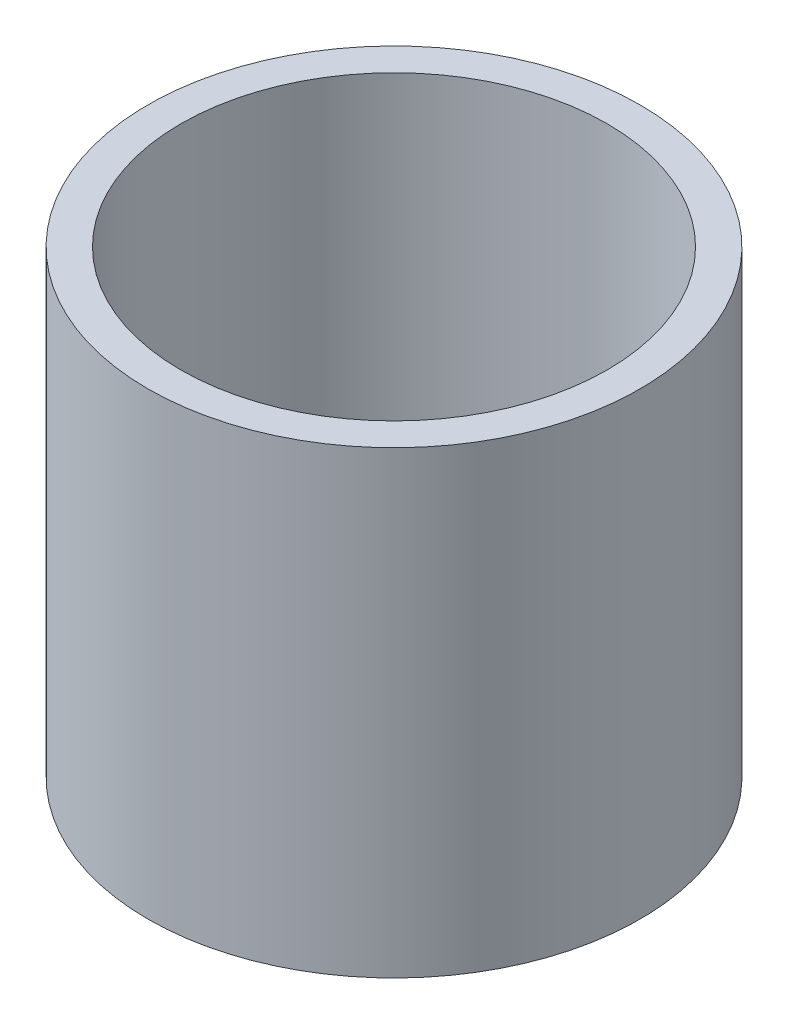
SolidWorks part; units mm, degrees
ref_plane "前视基准面" through (0, 0, 0) normal (0, 0, 1) x (1, 0, 0)
ref_plane "上视基准面" through (0, 0, 0) normal (0, 1, 0) x (1, 0, 0)
ref_plane "右视基准面" through (0, 0, 0) normal (1, 0, 0) x (0, 0, -1)
other "Configuration Table"
sketch "草图1" plane through (0, 0, 0) normal (0, 1, 0) x (1, 0, 0)
  circle A0 centre (0, 0) radius 37.5
  dimension "D1" = 75
extrude "凸台-拉伸1" add sketch "草图1" along normal blind 70
sketch "草图2" plane through (0, 70, 0) normal (0, 1, 0) x (1, 0, 0)
  circle A0 centre (0, 0) radius 32.5
  dimension "D1" = 65
extrude "切除-拉伸1" cut sketch "草图2" against normal blind 60
sketch "草图3" plane through (0, 0, 0) normal (0, -1, 0) x (1, 0, 0)
  circle A0 centre (0, 0) radius 14.5
extrude "切除-拉伸2" cut sketch "草图3" against normal blind 40
